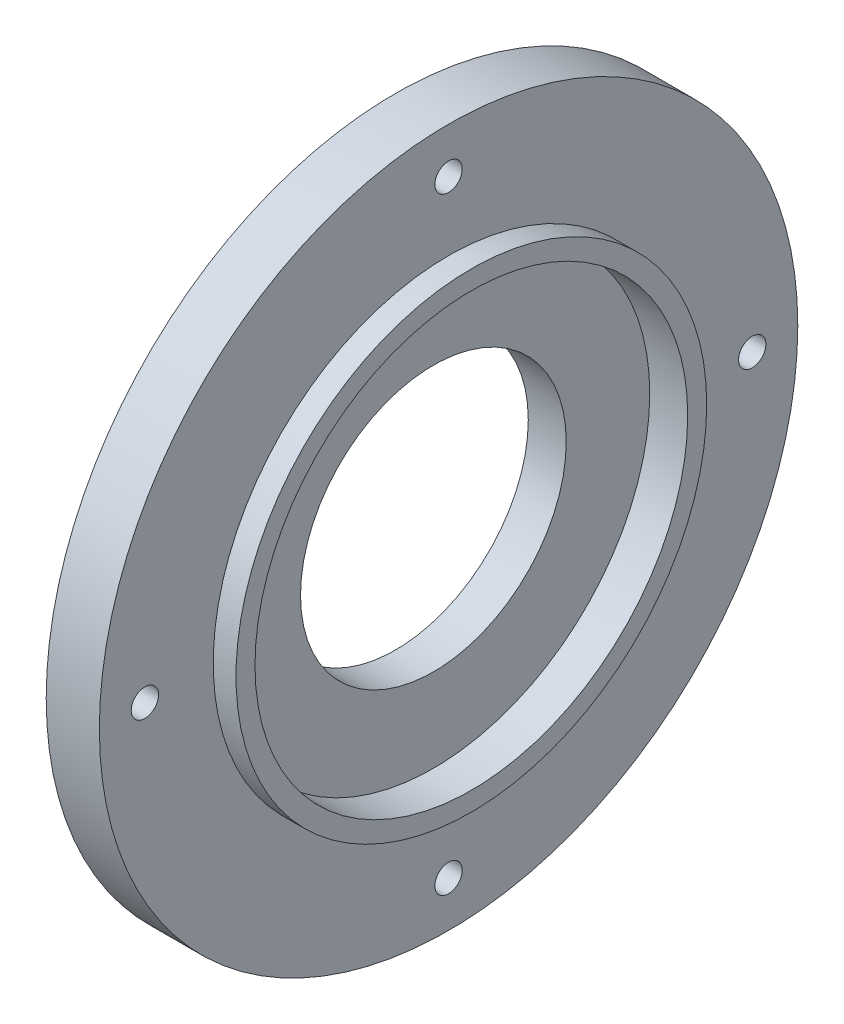
SolidWorks part; units mm, degrees
ref_plane "前视基准面" through (0, 0, 0) normal (0, 0, 1) x (1, 0, 0)
ref_plane "上视基准面" through (0, 0, 0) normal (0, 1, 0) x (1, 0, 0)
ref_plane "右视基准面" through (0, 0, 0) normal (1, 0, 0) x (0, 0, -1)
sketch "草图1" plane through (0, 0, 0) normal (1, 0, 0) x (0, 0, -1)
  circle A0 centre (0, 0) radius 17.5
  circle A1 centre (0, 0) radius 46
extrude "凸台-拉伸1" add sketch "草图1" along normal blind 5
sketch "草图2" plane through (5, 0, 0) normal (1, 0, 0) x (0, 0, -1)
  circle A0 centre (0, 0) radius 28.5
  circle A1 centre (0, 0) radius 31
extrude "凸台-拉伸2" add sketch "草图2" along normal blind 5
sketch "草图4" plane through (5, 0, 0) normal (1, 0, 0) x (0, 0, -1)
  circle A0 centre (0, 0) radius 31
  circle A1 centre (0, 0) radius 46
extrude "凸台-拉伸3" add sketch "草图4" along normal blind 2
sketch "草图5" plane through (0, 0, 0) normal (-1, 0, 0) x (0, 0, 1)
  line L0 (-96.6414, 0) -> (72.3707, 0) construction
  line L1 (72.3707, 0) -> (0, 58.5806) construction
  line L2 (0, 58.5806) -> (0, -57.4774) construction
  circle A4 centre (0, 40) radius 1.8
  circle A5 centre (40, 0) radius 1.8
  circle A6 centre (0, -40) radius 1.8
  circle A7 centre (-40, 0) radius 1.8
  point P16 (0, 0)
  dimension "D1" = 40
extrude "切除-拉伸1" cut sketch "草图5" against normal up to surface (7 mm away) up to face at (7, 0, -46)
